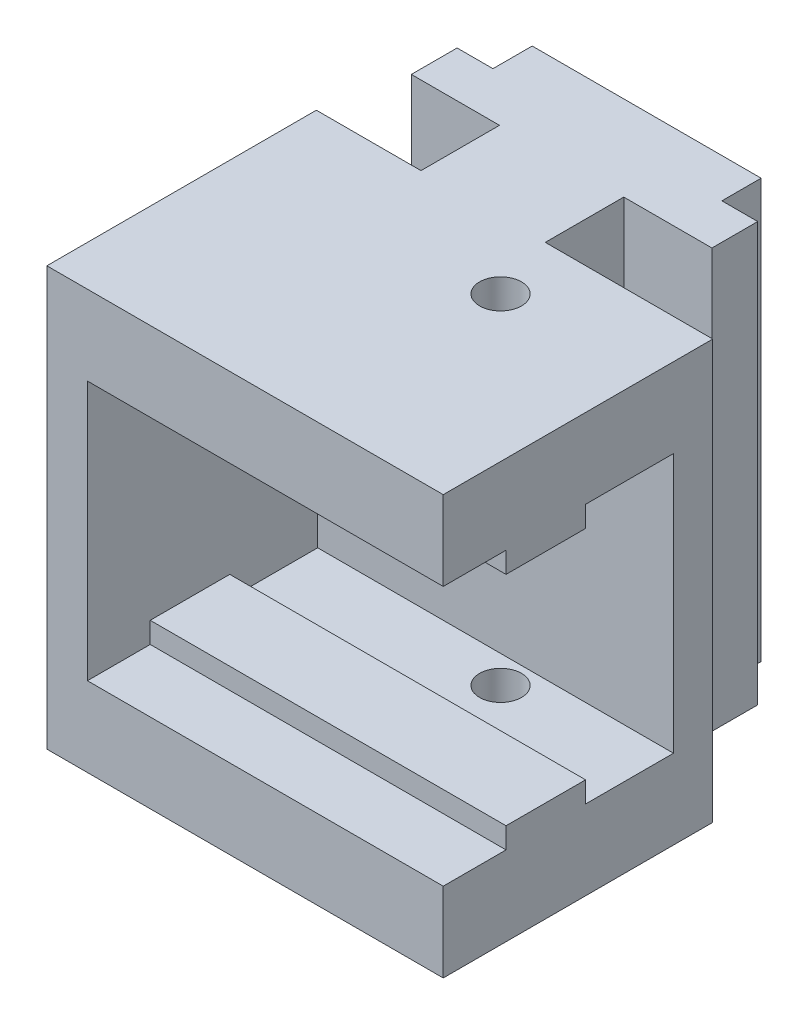
SolidWorks part; units mm, degrees
ref_plane "Front Plane" through (0, 0, 0) normal (0, 0, 1) x (1, 0, 0)
ref_plane "Top Plane" through (0, 0, 0) normal (0, 1, 0) x (1, 0, 0)
ref_plane "Right Plane" through (0, 0, 0) normal (1, 0, 0) x (0, 0, -1)
sketch "Sketch1" plane through (0, 0, 0) normal (0, 1, 0) x (1, 0, 0)
  line L1 (-10.1203, -10.9141) -> (10.1203, -10.9141)
  line L2 (-10.1203, -10.9141) -> (-10.1203, 10.9141)
  line L3 (-10.1203, 10.9141) -> (10.1203, 10.9141)
  line L4 (10.1203, -10.9141) -> (10.1203, 10.9141)
  line L5 (-10.1203, -10.9141) -> (10.1203, 10.9141) construction
  line L6 (-10.1203, 10.9141) -> (10.1203, -10.9141) construction
  point P0 (0, 0)
  dimension "D1" = 20.2406
  dimension "D2" = 21.8281
extrude "Boss-Extrude1" add sketch "Sketch1" along normal blind 20.32
sketch "Sketch2" plane through (0, 20.32, 0) normal (0, 1, 0) x (1, 0, 0)
  line L0 (10.1203, -10.9141) -> (10.1203, 0.9922) construction
  line L1 (10.1203, -10.9141) -> (10.1203, 10.9141) construction
  line L2 (10.1203, 0.9922) -> (3.7703, 0.9922)
  line L3 (3.7703, 0.9922) -> (3.7703, 5.7547)
  line L4 (3.7703, 5.7547) -> (9.1203, 5.7547)
  line L5 (0, 0) -> (0, -50000) construction
  line L6 (10.1203, 5.7547) -> (10.1203, 8.5328) construction
  line L7 (9.1203, 8.5328) -> (6.9453, 8.5328)
  line L8 (6.9453, 8.5328) -> (6.9453, 10.9141)
  line L9 (10.1203, 10.9141) -> (-10.1203, 10.9141) construction
  line L10 (6.9453, 10.9141) -> (10.1203, 10.9141)
  line L11 (10.1203, 10.9141) -> (10.1203, 8.5328)
  line L12 (10.1203, 5.7547) -> (10.1203, 0.9922)
  line L13 (-6.9453, 10.9141) -> (-10.1203, 10.9141)
  line L14 (-6.9453, 8.5328) -> (-6.9453, 10.9141)
  line L15 (-9.1203, 8.5328) -> (-6.9453, 8.5328)
  line L16 (-10.1203, 10.9141) -> (-10.1203, 8.5328)
  line L17 (-3.7703, 5.7547) -> (-9.1203, 5.7547)
  line L18 (-3.7703, 0.9922) -> (-3.7703, 5.7547)
  line L19 (-10.1203, 0.9922) -> (-3.7703, 0.9922)
  line L20 (-10.1203, 5.7547) -> (-10.1203, 0.9922)
  line L23 (10.1203, 8.5328) -> (10.1203, 5.7547)
  line L25 (9.1203, 8.5328) -> (9.1203, 5.7547)
  line L26 (-9.1203, 8.5328) -> (-9.1203, 5.7547)
  line L28 (-10.1203, 8.5328) -> (-10.1203, 5.7547)
  dimension "D1" = 11.9062
  dimension "D2" = 4.7625
  dimension "D3" = 6.35
  dimension "D4" = 2.7781
  dimension "D5" = 3.175
  dimension "D6" = 1
extrude "Cut-Extrude1" cut sketch "Sketch2" against normal blind 20.32
sketch "Sketch4" plane through (0, 0, 10.9141) normal (0, 0, 1) x (1, 0, 0)
  line L1 (-10.1203, 20.32) -> (10.1203, 20.32)
  line L2 (-10.1203, 20.32) -> (-10.1203, 0)
  line L3 (-10.1203, 0) -> (10.1203, 0)
  line L4 (10.1203, 20.32) -> (10.1203, 0)
extrude "Boss-Extrude2" add sketch "Sketch4" along normal blind 4.445
sketch "Sketch6" plane through (0, 20.32, 0) normal (0, 1, 0) x (1, 0, 0)
  line L0 (-10.1203, -15.3591) -> (-10.1203, 0.9922)
  line L1 (-10.1203, 0.9922) -> (-3.7703, 0.9922)
  line L2 (-3.7703, 0.9922) -> (-3.7703, 5.7547)
  line L3 (-3.7703, 5.7547) -> (-9.1203, 5.7547)
  line L4 (-9.1203, 5.7547) -> (-9.1203, 8.5328)
  line L5 (-9.1203, 8.5328) -> (-6.9453, 8.5328)
  line L6 (-6.9453, 8.5328) -> (-6.9453, 10.9141)
  line L7 (-6.9453, 10.9141) -> (6.9453, 10.9141)
  line L8 (6.9453, 10.9141) -> (6.9453, 8.5328)
  line L9 (6.9453, 8.5328) -> (9.1203, 8.5328)
  line L10 (9.1203, 8.5328) -> (9.1203, 5.7547)
  line L11 (9.1203, 5.7547) -> (3.7703, 5.7547)
  line L12 (3.7703, 5.7547) -> (3.7703, 0.9922)
  line L13 (3.7703, 0.9922) -> (10.1203, 0.9922)
  line L14 (10.1203, 0.9922) -> (10.1203, -15.3591)
  line L15 (10.1203, -15.3591) -> (-10.1203, -15.3591)
extrude "Boss-Extrude3" add sketch "Sketch6" along normal blind 2.54
sketch "Sketch7" plane through (0, 0, 0) normal (0, -1, 0) x (1, 0, 0)
  line L0 (-10.1203, -0.9922) -> (-10.1203, 15.3591)
  line L1 (-10.1203, 15.3591) -> (10.1203, 15.3591)
  line L2 (10.1203, 15.3591) -> (10.1203, -0.9922)
  line L3 (10.1203, -0.9922) -> (3.7703, -0.9922)
  line L4 (3.7703, -0.9922) -> (3.7703, -5.7547)
  line L5 (3.7703, -5.7547) -> (9.1203, -5.7547)
  line L6 (9.1203, -5.7547) -> (9.1203, -8.5328)
  line L7 (9.1203, -8.5328) -> (6.9453, -8.5328)
  line L8 (6.9453, -8.5328) -> (6.9453, -10.9141)
  line L9 (6.9453, -10.9141) -> (-6.9453, -10.9141)
  line L10 (-6.9453, -10.9141) -> (-6.9453, -8.5328)
  line L11 (-6.9453, -8.5328) -> (-9.1203, -8.5328)
  line L12 (-9.1203, -8.5328) -> (-9.1203, -5.7547)
  line L13 (-9.1203, -5.7547) -> (-3.7703, -5.7547)
  line L14 (-3.7703, -5.7547) -> (-3.7703, -0.9922)
  line L15 (-3.7703, -0.9922) -> (-10.1203, -0.9922)
extrude "Boss-Extrude4" add sketch "Sketch7" along normal blind 2.54
sketch "Sketch8" plane through (10.1203, 0, 0) normal (1, 0, 0) x (0, 0, -1)
  line L1 (-15.3591, -2.54) -> (0.9922, -2.54)
  line L2 (-15.3591, -2.54) -> (-15.3591, 22.86)
  line L3 (-15.3591, 22.86) -> (0.9922, 22.86)
  line L4 (0.9922, -2.54) -> (0.9922, 22.86)
extrude "Boss-Extrude5" add sketch "Sketch8" along normal blind 7.62
sketch "Sketch10" plane through (0, -2.54, 0) normal (0, -1, 0) x (1, 0, 0)
  line L0 (-10.1203, 15.3591) -> (-10.1203, -0.9922) construction
  line L1 (3.7703, -0.9922) -> (17.7403, -0.9922) construction
  circle A0 centre (5.1197, 3.0718) radius 1.27
  dimension "D2" = 2.54
  dimension "D1" = 15.24
  dimension "D3" = 4.064
extrude "Cut-Extrude3" cut sketch "Sketch10" against normal through all
sketch "Sketch12" plane through (17.7403, 0, 0) normal (1, 0, 0) x (0, 0, -1)
  line L0 (-15.3591, 18.034) -> (-15.3591, 2.286)
  line L1 (-15.3591, 22.86) -> (-15.3591, -2.54) construction
  line L2 (-15.3591, 18.034) -> (-11.5491, 18.034)
  line L3 (-11.5491, 18.034) -> (-11.5491, 16.764)
  line L4 (-11.5491, 16.764) -> (-6.7231, 16.764)
  line L5 (-6.7231, 16.764) -> (-6.7231, 18.034)
  line L6 (-6.7231, 18.034) -> (-1.3891, 18.034)
  line L7 (-1.3891, 18.034) -> (-1.3891, 2.286)
  line L8 (-1.3891, 2.286) -> (-6.7231, 2.286)
  line L9 (-6.7231, 2.286) -> (-6.7231, 3.556)
  line L10 (-6.7231, 3.556) -> (-11.5491, 3.556)
  line L11 (-11.5491, 3.556) -> (-11.5491, 2.286)
  line L12 (-11.5491, 2.286) -> (-15.3591, 2.286)
  point P5 (-15.3591, 10.16)
  point P14 (-15.3591, 10.16)
  dimension "D1" = 15.748
  dimension "D2" = 3.81
  dimension "D3" = 4.826
  dimension "D4" = 5.334
  dimension "D5" = 1.27
extrude "Cut-Extrude4" cut sketch "Sketch12" against normal blind 25.4
sketch "Sketch14" plane through (17.7403, 0, 0) normal (1, 0, 0) x (0, 0, -1)
  line L1 (0.9922, 22.86) -> (-15.3591, 22.86)
  line L2 (0.9922, 22.86) -> (0.9922, -2.54)
  line L3 (0.9922, -2.54) -> (-15.3591, -2.54)
  line L4 (-15.3591, 22.86) -> (-15.3591, -2.54)
extrude "Cut-Extrude5" cut sketch "Sketch14" against normal blind 3.81
